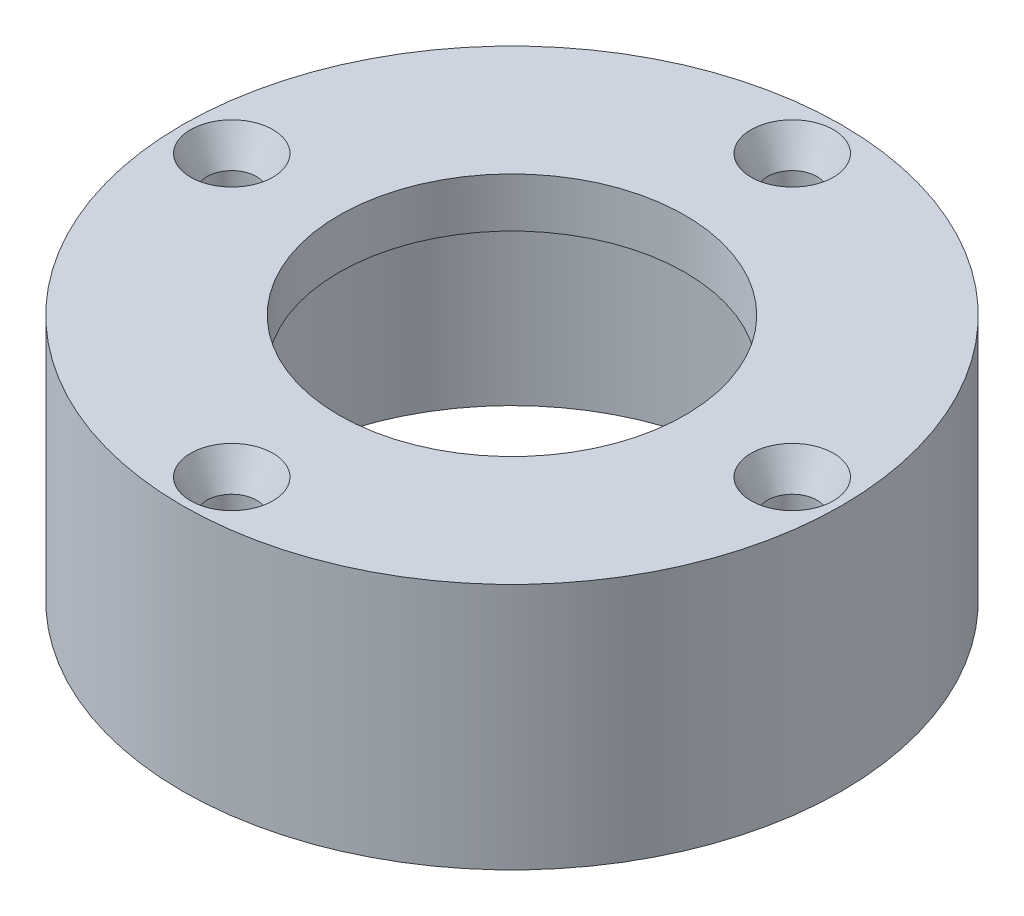
SolidWorks part; units mm, degrees
ref_plane "Front Plane" through (0, 0, 0) normal (0, 0, 1) x (1, 0, 0)
ref_plane "Top Plane" through (0, 0, 0) normal (0, 1, 0) x (1, 0, 0)
ref_plane "Right Plane" through (0, 0, 0) normal (1, 0, 0) x (0, 0, -1)
sketch "Sketch1" plane through (0, 0, 0) normal (0, 1, 0) x (1, 0, 0)
  circle A0 centre (0, 0) radius 20
extrude "Boss-Extrude1" add sketch "Sketch1" along normal blind 15
sketch "Sketch4" plane through (0, 0, 0) normal (0, -1, 0) x (1, 0, 0)
  circle A0 centre (0, 0) radius 14.5
extrude "Cut-Extrude3" cut sketch "Sketch4" against normal blind 12
sketch "Sketch5" plane through (0, 15, 0) normal (0, 1, 0) x (1, 0, 0)
  circle A0 centre (0, 0) radius 10.5
extrude "Cut-Extrude4" cut sketch "Sketch5" against normal blind 12
sketch "Sketch6" plane through (0, 15, 0) normal (0, 1, 0) x (1, 0, 0)
  line L0 (0, 0) -> (0, 28.6341) construction
  line L1 (0, 0) -> (42.7374, 0) construction
  circle A0 centre (0, 17) radius 1.5
  circle A1 centre (17, 0) radius 1.5
  circle A2 centre (0, -17) radius 1.5
  circle A3 centre (-17, 0) radius 1.5
  point P18 (0, 0)
  dimension "D1" = 17
extrude "Cut-Extrude5" cut sketch "Sketch6" against normal through all
sketch "Sketch7" plane through (0, 15, 0) normal (0, 1, 0) x (1, 0, 0)
  circle A0 centre (0, 17) radius 2.5
  circle A1 centre (17, 0) radius 2.5
  circle A2 centre (0, -17) radius 2.5
  circle A3 centre (-17, 0) radius 2.5
  point P12 (0, 0)
  dimension "D1" = 4
extrude "Cut-Extrude7" cut sketch "Sketch7" against normal blind 2 draft 27
